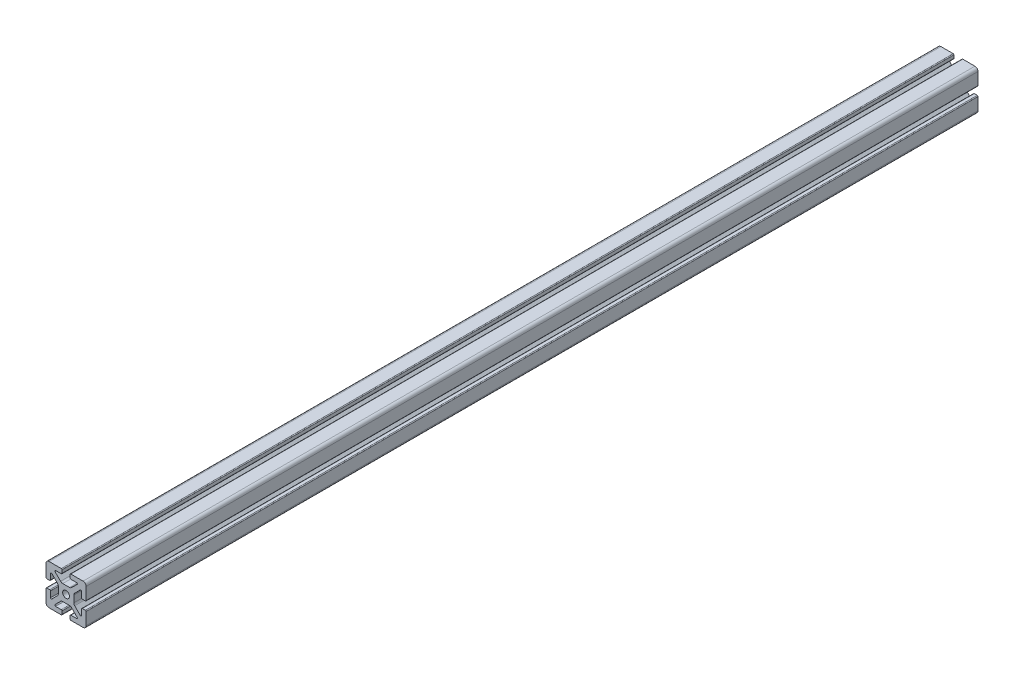
SolidWorks part; units mm, degrees
ref_plane "Front Plane" through (0, 0, 0) normal (0, 0, 1) x (1, 0, 0)
ref_plane "Top Plane" through (0, 0, 0) normal (0, 1, 0) x (1, 0, 0)
ref_plane "Right Plane" through (0, 0, 0) normal (1, 0, 0) x (0, 0, -1)
sketch "Sketch1" plane through (0, 0, 0) normal (0, 0, 1) x (1, 0, 0)
  line L0 (0, 20) -> (0, -20) construction
  line L1 (-20, 0) -> (20, 0) construction
  line L2 (-20, 16.952) -> (-20, 4.7625)
  line L3 (-16.952, 20) -> (-4.7625, 20)
  line L4 (-4.0005, 19.238) -> (-4.0005, 16.2662)
  line L5 (-4.7625, 15.5042) -> (-10.4856, 15.5042)
  line L6 (-11.0244, 14.2034) -> (-5.456, 8.6351)
  line L7 (-14.2034, 11.0244) -> (-8.6351, 5.456)
  line L8 (-15.5042, 10.4856) -> (-15.5042, 4.7625)
  line L9 (-16.2662, 4.0005) -> (-19.238, 4.0005)
  line L10 (0, 0) -> (-20, 20) construction
  line L11 (-3.3367, 7.7572) -> (3.3367, 7.7572)
  line L12 (-7.7572, 3.3367) -> (-7.7572, -3.3367)
  line L13 (16.2662, 4.0005) -> (19.238, 4.0005)
  line L14 (15.5042, 10.4856) -> (15.5042, 4.7625)
  line L15 (20, 16.952) -> (20, 4.7625)
  line L16 (16.952, 20) -> (4.7625, 20)
  line L17 (4.0005, 19.238) -> (4.0005, 16.2662)
  line L18 (4.7625, 15.5042) -> (10.4856, 15.5042)
  line L19 (7.7572, 3.3367) -> (7.7572, -3.3367)
  line L20 (11.0244, 14.2034) -> (5.456, 8.6351)
  line L21 (14.2034, 11.0244) -> (8.6351, 5.456)
  line L22 (-16.2662, -4.0005) -> (-19.238, -4.0005)
  line L23 (-15.5042, -10.4856) -> (-15.5042, -4.7625)
  line L24 (-14.2034, -11.0244) -> (-8.6351, -5.456)
  line L25 (-11.0244, -14.2034) -> (-5.456, -8.6351)
  line L26 (-4.7625, -15.5042) -> (-10.4856, -15.5042)
  line L27 (-4.0005, -19.238) -> (-4.0005, -16.2662)
  line L28 (-16.952, -20) -> (-4.7625, -20)
  line L29 (-20, -16.952) -> (-20, -4.7625)
  line L30 (20, -16.952) -> (20, -4.7625)
  line L31 (16.952, -20) -> (4.7625, -20)
  line L32 (4.0005, -19.238) -> (4.0005, -16.2662)
  line L33 (4.7625, -15.5042) -> (10.4856, -15.5042)
  line L34 (11.0244, -14.2034) -> (5.456, -8.6351)
  line L35 (14.2034, -11.0244) -> (8.6351, -5.456)
  line L36 (15.5042, -10.4856) -> (15.5042, -4.7625)
  line L37 (16.2662, -4.0005) -> (19.238, -4.0005)
  line L38 (-3.3367, -7.7572) -> (3.3367, -7.7572)
  circle A0 centre (0, 0) radius 3.4036
  arc A1 (-20, 16.952) -> (-16.952, 20) centre (-16.952, 16.952) cw
  arc A2 (-14.2034, 11.0244) -> (-15.5042, 10.4856) centre (-14.7422, 10.4856) ccw
  arc A3 (-10.4856, 15.5042) -> (-11.0244, 14.2034) centre (-10.4856, 14.7422) ccw
  arc A4 (-4.7625, 20) -> (-4.0005, 19.238) centre (-4.7625, 19.238) cw
  arc A5 (-20, 4.7625) -> (-19.238, 4.0005) centre (-19.238, 4.7625) ccw
  arc A6 (-15.5042, 4.7625) -> (-16.2662, 4.0005) centre (-16.2662, 4.7625) cw
  arc A7 (-4.0005, 16.2662) -> (-4.7625, 15.5042) centre (-4.7625, 16.2662) cw
  arc A8 (-3.3367, 7.7572) -> (-5.456, 8.6351) centre (-3.3367, 10.7544) cw
  arc A9 (-7.7572, 3.3367) -> (-8.6351, 5.456) centre (-10.7544, 3.3367) ccw
  arc A10 (15.5042, 4.7625) -> (16.2662, 4.0005) centre (16.2662, 4.7625) ccw
  arc A11 (20, 4.7625) -> (19.238, 4.0005) centre (19.238, 4.7625) cw
  arc A12 (20, 16.952) -> (16.952, 20) centre (16.952, 16.952) ccw
  arc A13 (4.7625, 20) -> (4.0005, 19.238) centre (4.7625, 19.238) ccw
  arc A14 (4.0005, 16.2662) -> (4.7625, 15.5042) centre (4.7625, 16.2662) ccw
  arc A15 (3.3367, 7.7572) -> (5.456, 8.6351) centre (3.3367, 10.7544) ccw
  arc A16 (7.7572, 3.3367) -> (8.6351, 5.456) centre (10.7544, 3.3367) cw
  arc A17 (14.2034, 11.0244) -> (15.5042, 10.4856) centre (14.7422, 10.4856) cw
  arc A18 (10.4856, 15.5042) -> (11.0244, 14.2034) centre (10.4856, 14.7422) cw
  arc A19 (-7.7572, -3.3367) -> (-8.6351, -5.456) centre (-10.7544, -3.3367) cw
  arc A20 (-3.3367, -7.7572) -> (-5.456, -8.6351) centre (-3.3367, -10.7544) ccw
  arc A21 (-4.0005, -16.2662) -> (-4.7625, -15.5042) centre (-4.7625, -16.2662) ccw
  arc A22 (-15.5042, -4.7625) -> (-16.2662, -4.0005) centre (-16.2662, -4.7625) ccw
  arc A23 (-20, -4.7625) -> (-19.238, -4.0005) centre (-19.238, -4.7625) cw
  arc A24 (-4.7625, -20) -> (-4.0005, -19.238) centre (-4.7625, -19.238) ccw
  arc A25 (-10.4856, -15.5042) -> (-11.0244, -14.2034) centre (-10.4856, -14.7422) cw
  arc A26 (-14.2034, -11.0244) -> (-15.5042, -10.4856) centre (-14.7422, -10.4856) cw
  arc A27 (-20, -16.952) -> (-16.952, -20) centre (-16.952, -16.952) ccw
  arc A28 (20, -16.952) -> (16.952, -20) centre (16.952, -16.952) cw
  arc A29 (14.2034, -11.0244) -> (15.5042, -10.4856) centre (14.7422, -10.4856) ccw
  arc A30 (10.4856, -15.5042) -> (11.0244, -14.2034) centre (10.4856, -14.7422) ccw
  arc A31 (4.7625, -20) -> (4.0005, -19.238) centre (4.7625, -19.238) cw
  arc A32 (20, -4.7625) -> (19.238, -4.0005) centre (19.238, -4.7625) ccw
  arc A33 (15.5042, -4.7625) -> (16.2662, -4.0005) centre (16.2662, -4.7625) cw
  arc A34 (4.0005, -16.2662) -> (4.7625, -15.5042) centre (4.7625, -16.2662) cw
  arc A35 (3.3367, -7.7572) -> (5.456, -8.6351) centre (3.3367, -10.7544) cw
  arc A36 (7.7572, -3.3367) -> (8.6351, -5.456) centre (10.7544, -3.3367) ccw
  point P29 (-20, 4.0005)
  point P32 (-15.5042, 4.0005)
  point P36 (-4.5782, 7.7572)
  point P68 (0, 7.7572)
  dimension "D4" = 6.8072
  dimension "D5" = 3.048
  dimension "D6" = 0.762
  dimension "D9" = 0.762
  dimension "D10" = 0.762
  dimension "D11" = 4.4958
  dimension "D13" = 2.9972
  dimension "D1" = 40
  dimension "D2" = 40
  dimension "D3" = 12.2428
  dimension "D7" = 8.001
  dimension "D8" = 4.4958
extrude "Extrude1" add sketch "Sketch1" along normal mid plane 889
equation "\"D2@Sketch1\" = \"D1@Sketch1\""
